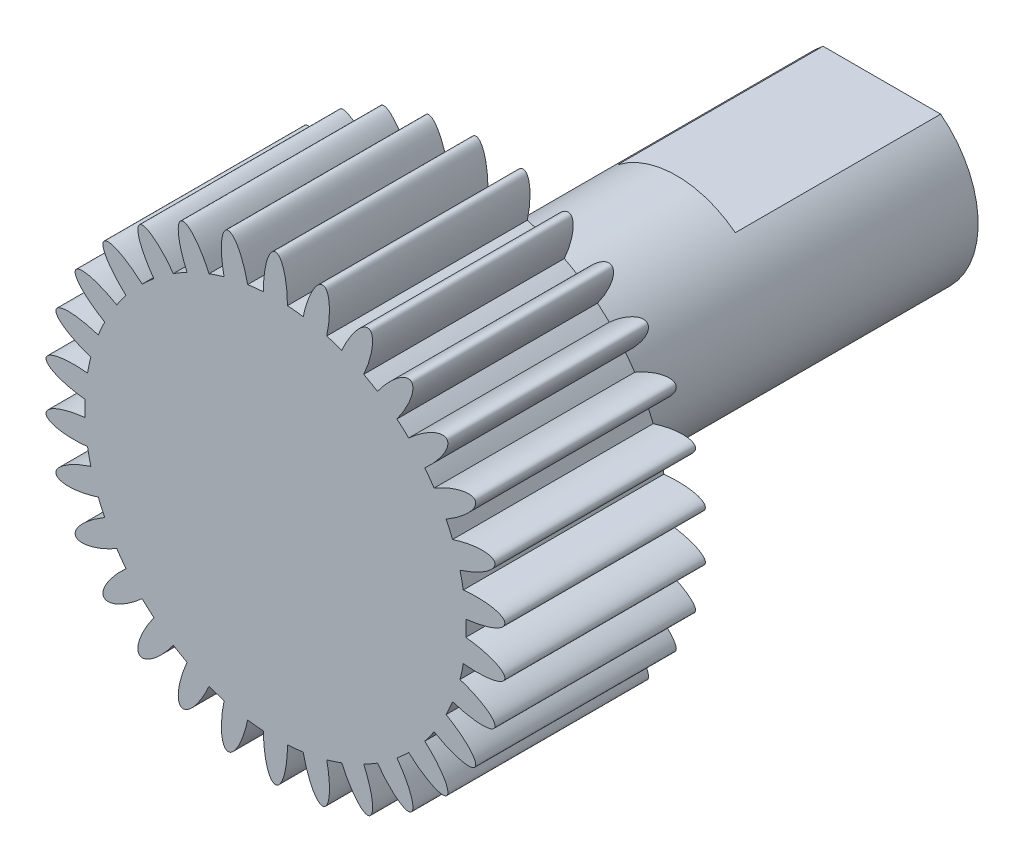
SolidWorks part; units mm, degrees
ref_plane "Front Plane" through (0, 0, 0) normal (0, 0, 1) x (1, 0, 0)
ref_plane "Top Plane" through (0, 0, 0) normal (0, 1, 0) x (1, 0, 0)
ref_plane "Right Plane" through (0, 0, 0) normal (1, 0, 0) x (0, 0, -1)
sketch "Sketch1" plane through (0, 0, 0) normal (0, 0, 1) x (1, 0, 0)
  line L0 (-3.81, 5.08) -> (3.81, 5.08) construction
  line L1 (55, 0) -> (-55, 0) construction
  line L2 (-3.7244, 4.826) -> (3.7244, 4.826)
  arc A0 (-3.81, 5.08) -> (3.81, 5.08) centre (0, 0) ccw construction
  arc A1 (-3.7244, 4.826) -> (3.7244, 4.826) centre (0, 0) ccw
  dimension "D1" = 12.7
  dimension "D2" = 5.08
  dimension "D3" = 0.254
extrude "Boss-Extrude1" add sketch "Sketch1" along normal blind 13
sketch "Sketch2" plane through (0, 0, 13) normal (0, 0, 1) x (1, 0, 0)
  circle A0 centre (0, 0) radius 6.096
extrude "Boss-Extrude2" add sketch "Sketch2" along normal blind 12.7
sketch "Sketch3" plane through (0, 0, 25.7) normal (0, 0, 1) x (1, 0, 0)
  circle A0 centre (0, 0) radius 12.065
  dimension "D1" = 24.13
extrude "Boss-Extrude3" add sketch "Sketch3" along normal blind 12.7
ref_axis "Axis1" through (0, 0, 44.3205) along (0, 0, -1)
sketch "Sketch4" plane through (0, 0, 38.4) normal (0, 0, 1) x (1, 0, 0)
  line L0 (0, -6.7056) -> (0, 6.7056) construction
  circle A0 centre (0, 0) radius 12.065 construction
  ellipse E0 centre (0, 12.065) end of major axis (0, 14.605) minor radius 0.762
  dimension "D1" = 2.54
  dimension "D2" = 1.524
extrude "Boss-Extrude4" add sketch "Sketch4" against normal up to surface (12.7 mm away) up to face at (6.096, 0, 25.7)
pattern_circular "CirPattern1" count 30 over 360 about axis through (0, 0, 44.3205) along (0, 0, -1) of "Boss-Extrude4"
